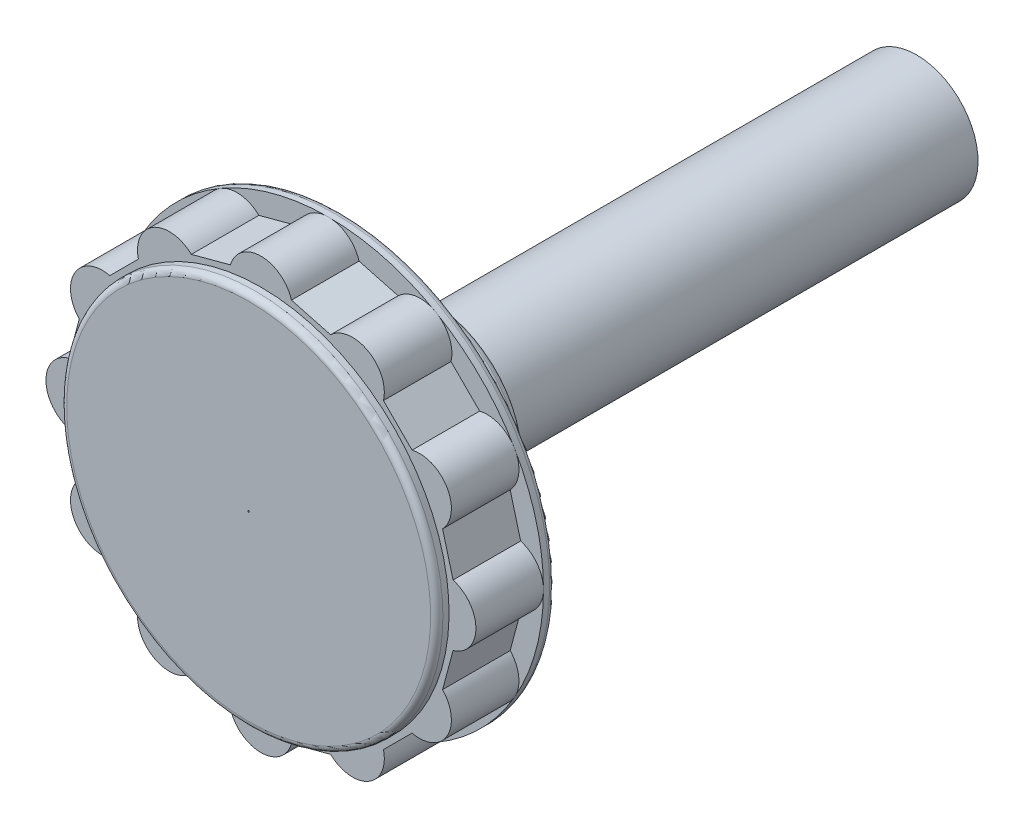
SolidWorks part; units mm, degrees
ref_plane "Front" through (0, 0, 0) normal (0, 0, 1) x (1, 0, 0)
ref_plane "Top" through (0, 0, 0) normal (0, 1, 0) x (1, 0, 0)
ref_plane "Right" through (0, 0, 0) normal (1, 0, 0) x (0, 0, -1)
sketch "Sketch4" plane through (0, 0, 0) normal (1, 0, 0) x (0, 0, -1)
  line L0 (0, 0) -> (0, 9.525)
  line L1 (0, 9.525) -> (-9.525, 9.525)
  line L2 (-9.525, 9.525) -> (-9.525, 22.225)
  line L3 (-9.525, 22.225) -> (-16.1925, 22.225)
  line L4 (-19.05, 0) -> (0, 0)
  line L5 (0, 0) -> (0, -9.525) construction
  line L6 (-19.05, 0) -> (-19.05, 22.225) construction
  line L7 (-9.525, -9.525) -> (-9.525, -22.225) construction
  line L8 (-19.05, 22.225) -> (-9.525, 22.225) construction
  line L9 (0, 0) -> (-19.05, 0) construction
  line L10 (-16.1925, 22.225) -> (-19.05, 22.225)
  line L11 (-19.05, 22.225) -> (-19.05, 0) construction
  line L12 (-19.05, 22.225) -> (-19.05, 0)
  arc A0 (-19.05, 0) -> (-16.1925, 22.225) centre (68.8093, 0) cw construction
revolve "Revolve2" add sketch "Sketch4" angle 360 about L9
ref_plane "Plane1" through (0, 0, 10.795) normal (0, 0, -1) x (-1, 0, 0)
ref_plane "Plane2" through (0, 0, 17.78) normal (0, 0, 1) x (1, 0, 0)
sketch "Sketch5" plane through (0, 0, 10.795) normal (0, 0, -1) x (-1, 0, 0)
  line L0 (0, 0) -> (0, 22.225) construction
  line L1 (0, 22.225) -> (0, 0) construction
  line L2 (0, 0) -> (-11.1125, 19.2474) construction
  line L3 (-3.1566, 19.8623) -> (-7.1975, 18.7796)
  line L4 (0, 0) -> (-5.177, 19.3209) construction
  line L5 (0, 22.225) -> (0, 42.0736)
  line L6 (0, 42.0736) -> (-21.0368, 36.4368)
  line L7 (-21.0368, 36.4368) -> (-11.1125, 19.2474)
  circle A0 centre (0, 0) radius 22.225 construction
  arc A1 (-3.1566, 19.8623) -> (0, 22.225) centre (0, 18.9351) cw
  arc A2 (-7.1975, 18.7796) -> (-11.1125, 19.2474) centre (-9.4675, 16.3982) ccw
  circle A3 centre (0, 0) radius 20.0025 construction
  circle A7 centre (0, 0) radius 22.225 construction
extrude "Cut-Extrude1" cut sketch "Sketch5" against normal up to surface (6.985 mm away)
pattern_circular "CirPattern1" count 12 over 360 about axis through (0, 0, 0) along (0, 0, 1) of "Cut-Extrude1"
sketch "Sketch6" plane through (0, 0, 0) normal (1, 0, 0) x (0, 0, -1)
  line L0 (-17.78, 22.225) -> (-17.78, 0)
  line L1 (-17.78, 0) -> (-19.05, 0)
  line L2 (-19.05, 0) -> (-19.05, 22.225)
  line L3 (-19.05, 22.225) -> (-17.78, 22.225)
  line L4 (0, 0) -> (-19.05, 0) construction
  line L6 (-17.78, 55) -> (-17.78, -55) construction
  line L7 (-9.525, 22.225) -> (-16.1925, 22.225) construction
revolve "Cut-Revolve3" cut sketch "Sketch6" angle 360 about L4
sketch "Sketch7" plane through (0, 0, 0) normal (1, 0, 0) x (0, 0, -1)
  line L0 (-17.78, 0) -> (-17.78, 19.4469)
  line L2 (-19.05, 22.225) -> (-19.05, 0) construction
  line L4 (-17.78, 19.4469) -> (-19.05, 19.4469)
  line L5 (-19.05, 19.4469) -> (-19.05, 0)
  line L6 (-19.05, 0) -> (-17.78, 0)
  line L7 (0, 0) -> (-19.05, 0) construction
  line L8 (-17.78, 0) -> (-17.78, -19.4469) construction
  line L10 (-17.78, -19.4469) -> (-19.05, -19.4469) construction
  line L11 (-19.05, -19.4469) -> (-19.05, 0) construction
  line L12 (-17.78, 22.225) -> (-17.78, 0) construction
  line L13 (-17.78, -3.1566) -> (-17.78, -7.1975) construction
revolve "Revolve3" add sketch "Sketch7" angle 360 about L7
sketch "Sketch8" plane through (0, 0, 0) normal (1, 0, 0) x (0, 0, -1)
  line L0 (0, 0) -> (0, 6.35)
  line L1 (0, 0) -> (0, 9.525) construction
  line L2 (0, 6.35) -> (-14.2875, 6.35)
  line L3 (-14.2875, 6.35) -> (-14.2875, 0)
  line L5 (-14.2875, 0) -> (0, 0)
  line L6 (0, 0) -> (0, -6.35) construction
  line L7 (0, 0) -> (0, -9.525) construction
  line L8 (0, 0) -> (-19.05, 0) construction
  line L12 (0, -6.35) -> (-14.2875, -6.35) construction
  line L13 (-14.2875, 6.35) -> (-14.2875, -6.35) construction
  dimension "Hole Dia" = 12.7
  dimension "Hole Depth" = 14.2875
fillet "Fillet1" radius 0.635 3 edges at (0, 19.4469, 19.05) (0, 22.225, 9.525) (0, 9.525, 0)
hole_wizard "1/2-13 Tapped Hole1" positions "Sketch10" profile "Sketch9" tap size "1/2-13" standard "ANSI Inch"
sketch "Sketch10" plane through (0, 0, 0) normal (0, 0, -1) x (-1, 0, 0)
  point P0 (0, 0)
sketch "Sketch9" plane through (0, 0, 0) normal (1, 0, 0) x (0, 1, 0)
  line L0 (0, 0) -> (0, 19.0945)
  line L1 (0, 19.0945) -> (5.3581, 15.875)
  line L2 (5.3581, 15.875) -> (5.3581, 0)
  line L5 (5.3581, 0) -> (0, 0)
  line L10 (0, 19.0945) -> (-5.3581, 15.875) construction
  line L11 (0, -6.35) -> (0, 107.95) construction
  dimension "Tap Drill Dia." = 10.7163
  dimension "Tap Drill Depth" = 15.875
  dimension "Drill Angle" = 118
sketch "Sketch11" plane through (0, 0, 0) normal (0, 0, -1) x (-1, 0, 0)
  circle A0 centre (0, 0) radius 6.35
  dimension "D1" = 12.7
extrude "Boss-Extrude1" add sketch "Sketch11" against normal blind 18 and the other way blind 50 separate body
equation "\"D1@Sketch4\" = \"C@Sketch4\"*.7"
equation "\"D4@Sketch5\" = \"D3@Sketch5\"/2.75"
equation "\"D6@Sketch5\" = \"A@Sketch4\"*.9"
equation "\"D1@Sketch7\" = \"A@Sketch4\"*.875"
